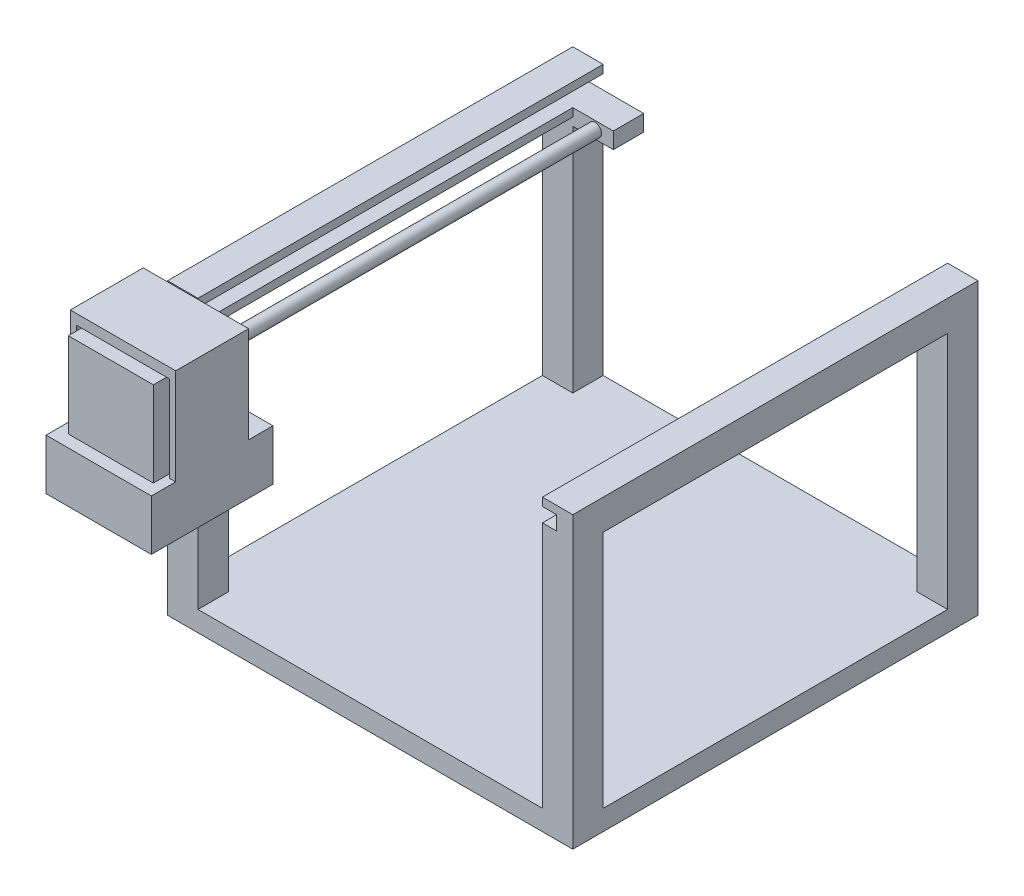
SolidWorks part; units mm, degrees
ref_plane "前视基准面" through (0, 0, 0) normal (0, 0, 1) x (1, 0, 0)
ref_plane "上视基准面" through (0, 0, 0) normal (0, 1, 0) x (1, 0, 0)
ref_plane "右视基准面" through (0, 0, 0) normal (1, 0, 0) x (0, 0, -1)
sketch "草图1" plane through (0, 0, 0) normal (0, 0, 1) x (1, 0, 0)
  line L1 (0, 0) -> (200, 0)
  line L2 (0, 0) -> (0, 10)
  line L3 (0, 10) -> (200, 10)
  line L4 (200, 0) -> (200, 10)
  dimension "D1" = 200
  dimension "D2" = 10
extrude "凸台-拉伸1" add sketch "草图1" against normal blind 200 contours L2 L1 L4 L3
sketch "草图2" plane through (0, 10, 0) normal (0, 1, 0) x (1, 0, 0)
  line L1 (0, 0) -> (15, 0)
  line L2 (0, 0) -> (0, 15)
  line L3 (0, 15) -> (15, 15)
  line L4 (15, 0) -> (15, 15)
  line L5 (200, 0) -> (185, 0)
  line L6 (200, 0) -> (200, 15)
  line L7 (200, 15) -> (185, 15)
  line L8 (185, 0) -> (185, 15)
  line L9 (200, 200) -> (185, 200)
  line L10 (200, 200) -> (200, 185)
  line L11 (200, 185) -> (185, 185)
  line L12 (185, 200) -> (185, 185)
  line L13 (0, 200) -> (15, 200)
  line L14 (0, 200) -> (0, 185)
  line L15 (0, 185) -> (15, 185)
  line L16 (15, 200) -> (15, 185)
  dimension "D1" = 15
  dimension "D2" = 15
  dimension "D3" = 15
  dimension "D4" = 15
  dimension "D5" = 15
  dimension "D6" = 15
  dimension "D7" = 15
  dimension "D8" = 15
extrude "凸台-拉伸2" add sketch "草图2" along normal blind 133
sketch "草图6" plane through (0, 0, -185) normal (0, 0, 1) x (1, 0, 0)
  line L0 (15, 143) -> (15, 10) construction
  line L1 (0, 143) -> (15, 143)
  line L2 (0, 143) -> (0, 128)
  line L3 (0, 128) -> (15, 128)
  line L4 (15, 143) -> (15, 128)
  line L5 (200, 143) -> (200, 10) construction
  line L6 (185, 143) -> (200, 143)
  line L7 (185, 143) -> (185, 128)
  line L8 (185, 128) -> (200, 128)
  line L9 (200, 143) -> (200, 128)
  dimension "D1" = 15
  dimension "D2" = 15
extrude "凸台-拉伸3" add sketch "草图6" along normal up to next
sketch "草图7" plane through (0, 0, 0) normal (0, 0, 1) x (1, 0, 0)
  line L0 (15, 143) -> (15, 10) construction
  line L1 (15, 139) -> (8, 139)
  line L2 (15, 139) -> (15, 132)
  line L3 (15, 132) -> (8, 132)
  line L4 (8, 139) -> (8, 132)
  line L10 (0, 143) -> (15, 143) construction
  line L11 (0, 128) -> (15, 128) construction
  line L12 (100, 10) -> (100, 0) construction
  line L15 (15, 10) -> (185, 10) construction
  line L16 (192, 139) -> (192, 132)
  line L17 (185, 132) -> (192, 132)
  line L18 (185, 139) -> (185, 132)
  line L19 (185, 139) -> (192, 139)
  point P16 (7.5, 128)
  point P18 (100, 10)
  dimension "D1" = 4
  dimension "D2" = 4
  dimension "D3" = 7
extrude "切除-拉伸1" cut sketch "草图7" against normal up to next
sketch "草图8" plane through (0, 0, 0) normal (0, 0, 1) x (1, 0, 0)
  line L0 (0, 0) -> (0, 143) construction
  line L1 (0, 107) -> (52, 107)
  line L2 (0, 107) -> (0, 82)
  line L3 (0, 82) -> (52, 82)
  line L4 (52, 107) -> (52, 82)
  line L5 (0, 143) -> (15, 143) construction
  dimension "D1" = 52
  dimension "D2" = 25
  dimension "D3" = 36
extrude "凸台-拉伸4" add sketch "草图8" along normal blind 60
sketch "草图9" plane through (0, 107, 0) normal (0, 1, 0) x (1, 0, 0)
  line L0 (52, -60) -> (52, 0) construction
  line L1 (52, -12) -> (49, -12)
  line L2 (52, -12) -> (52, -48)
  line L3 (52, -48) -> (49, -48)
  line L4 (49, -12) -> (49, -48)
  line L5 (0, -60) -> (0, 0) construction
  line L6 (0, -12) -> (3, -12)
  line L7 (0, -12) -> (0, -48)
  line L8 (0, -48) -> (3, -48)
  line L9 (3, -12) -> (3, -48)
  line L11 (15, 0) -> (185, 0) construction
  line L13 (5, -12) -> (47, -12)
  line L14 (5, -12) -> (5, -54)
  line L15 (5, -54) -> (47, -54)
  line L16 (47, -12) -> (47, -54)
  line M13 (52, -60) -> (52, 0)
  dimension "D1" = 3
  dimension "D2" = 3
  dimension "D3" = 36
  dimension "D4" = 12
  dimension "D5" = 46
  dimension "D6" = 42
  dimension "D7" = 42
  dimension "D8" = 2
extrude "凸台-拉伸7" add sketch "草图9" along normal blind 47.5 contours L1 L4 L3 M13 | L7 L6 L9 L8
sketch "草图12" plane through (0, 107, 0) normal (0, 1, 0) x (1, 0, 0)
  line L0 (3, -12) -> (3, -48) construction
  line L1 (5, -12) -> (47, -12)
  line L2 (5, -12) -> (5, -54)
  line L3 (5, -54) -> (47, -54)
  line L4 (47, -12) -> (47, -54)
  line L5 (52, -12) -> (49, -12) construction
  dimension "D1" = 42
  dimension "D2" = 2
  dimension "D3" = 42
extrude "凸台-拉伸8" add sketch "草图12" along normal blind 42 contours L2 L1 L4 L3
sketch "草图13" plane through (0, 0, 12) normal (0, 0, -1) x (-1, 0, 0)
  line L0 (-26, 107) -> (-26, 149) construction
  line L1 (-5, 107) -> (-47, 107) construction
  line L2 (-5, 149) -> (-47, 149) construction
  line L3 (-47, 128) -> (-26, 128) construction
  line L4 (-47, 149) -> (-47, 107) construction
  circle A0 centre (-26, 128) radius 3.175
  dimension "D1" = 6.35
sketch "草图14" plane through (49, 0, 0) normal (-1, 0, 0) x (0, 0, 1)
  line L0 (48, 154.5) -> (48, 107) construction
  line L1 (12, 154.5) -> (48, 154.5)
  line L2 (12, 154.5) -> (12, 149.5)
  line L3 (12, 149.5) -> (48, 149.5)
  line L4 (48, 154.5) -> (48, 149.5)
  dimension "D1" = 5
extrude "凸台-拉伸9" add sketch "草图14" along normal up to next contours L2 L1 L4 L3
sketch "草图15" plane through (0, 0, -200) normal (0, 0, -1) x (-1, 0, 0)
  line L1 (-15, 132) -> (-35, 132)
  line L2 (-15, 132) -> (-15, 124)
  line L3 (-15, 124) -> (-35, 124)
  line L4 (-35, 132) -> (-35, 124)
  dimension "D1" = 8
  dimension "D2" = 20
extrude "凸台-拉伸10" add sketch "草图15" against normal blind 15 contours L2 L1 L4 L3
extrude "凸台-拉伸11" add sketch "草图13" along normal up to next contours A0
